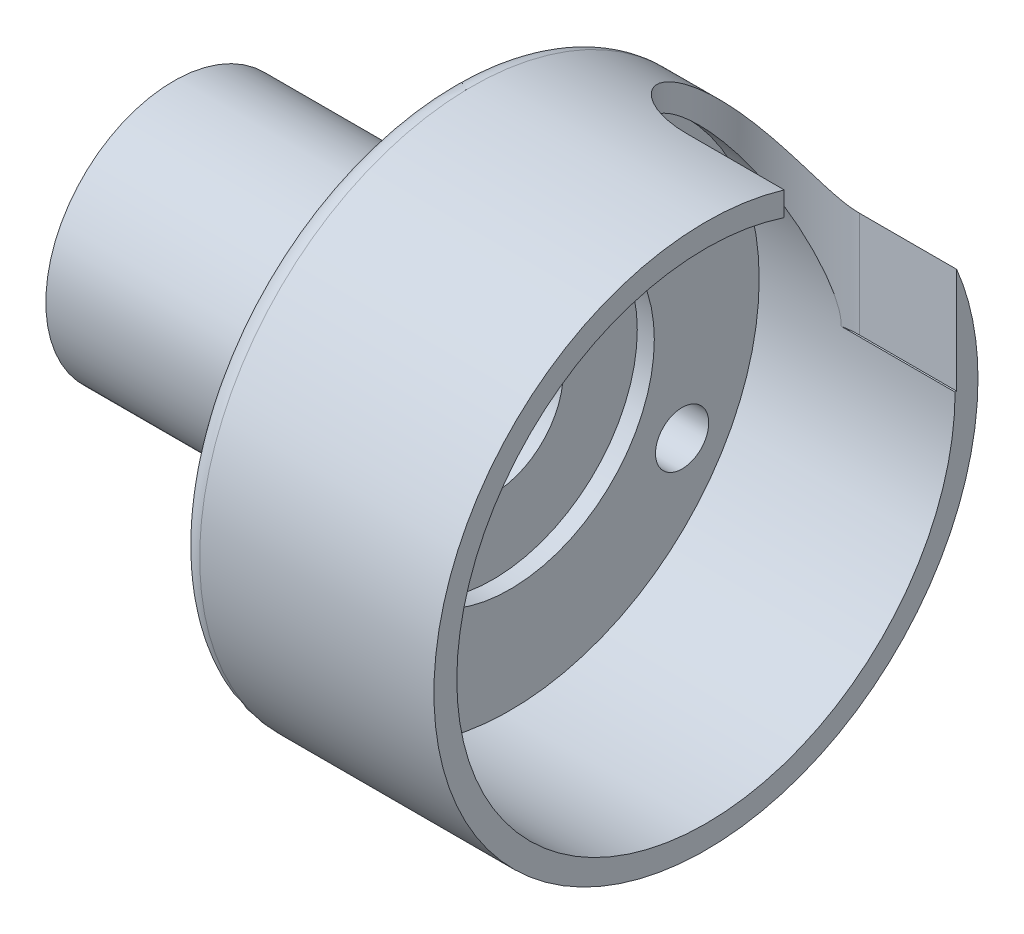
SolidWorks part; units mm, degrees
ref_plane "Front Plane" through (0, 0, 0) normal (0, 0, 1) x (1, 0, 0)
ref_plane "Top Plane" through (0, 0, 0) normal (0, 1, 0) x (1, 0, 0)
ref_plane "Right Plane" through (0, 0, 0) normal (1, 0, 0) x (0, 0, -1)
sketch "Sketch3" plane through (0, 0, 0) normal (1, 0, 0) x (0, 0, -1)
  circle A0 centre (0, 0) radius 6
  circle A1 centre (0, 0) radius 3.3
  dimension "D1" = 12
  dimension "D2" = 6.6
extrude "Boss-Extrude3" add sketch "Sketch3" along normal blind 10 and the other way blind 5 contours A1 | A0
sketch "Sketch10" plane through (10, 0, 0) normal (1, 0, 0) x (0, 0, -1)
  circle A0 centre (0, 0) radius 12.775
  circle A1 centre (0, 0) radius 2.1
  circle A2 centre (0, 0) radius 3.65
  dimension "D1" = 1.55
  dimension "D2" = 4.2
  dimension "D3" = 25.55
extrude "Boss-Extrude5" add sketch "Sketch10" against normal blind 2 contours A0
sketch "Sketch11" plane through (10, 0, 0) normal (1, 0, 0) x (0, 0, -1)
  circle A0 centre (0, 0) radius 6.775
  circle A1 centre (0, 0) radius 11.275
  circle M2 centre (0, 0) radius 3.3
  dimension "D1" = 13.55
  dimension "D2" = 22.55
extrude "Boss-Extrude6" add sketch "Sketch11" along normal blind 0.8 contours M2 | A0 M2 | A1
sketch "Sketch12" plane through (10.8, 0, 0) normal (1, 0, 0) x (0, 0, -1)
  line L1 (0, 9.33) -> (-8.08, -4.665)
  line L2 (-8.08, -4.665) -> (8.08, -4.665)
  line L3 (8.08, -4.665) -> (0, 9.33)
  circle A0 centre (0, 0) radius 4.665 construction
  circle A1 centre (0, 0) radius 11.275 construction
  circle A2 centre (-8.08, -4.665) radius 1.25
  circle A3 centre (8.08, -4.665) radius 1.25
  circle A4 centre (0, 9.33) radius 1.25
  dimension "D2" = 2.5
  dimension "D3" = 2.5
  dimension "D4" = 2.5
  dimension "D1" = 9.33
extrude "Cut-Extrude2" cut sketch "Sketch12" against normal blind 2.75 contours L2 A3 L3 | L3 A4 L1 | L1 A4 L3 | L3 A3 L2 | A2
fillet "Fillet3" radius 1 1 edges at (8, 0, -12.775)
sketch "Sketch13" plane through (10, 0, 0) normal (1, 0, 0) x (0, 0, -1)
  circle A0 centre (0, 0) radius 11.275 construction
  circle A1 centre (0, 0) radius 11.275
  circle A2 centre (0, 0) radius 12.775 construction
  circle A3 centre (0, 0) radius 12.775
extrude "Boss-Extrude7" add sketch "Sketch13" along normal blind 10
sketch "Sketch14" plane through (20, 0, 0) normal (1, 0, 0) x (0, 0, -1)
  circle A0 centre (0, 0) radius 11.7
  dimension "D1" = 23.4
extrude "Cut-Extrude3" cut sketch "Sketch14" against normal up to surface (9.2 mm away) up to face at (10.8, 9.33, -1.25)
sketch "Sketch15" plane through (0, 0, 0) normal (0, 1, 0) x (1, 0, 0)
  line L0 (15.4301, 3.675) -> (20, 3.675)
  line L1 (20, -12.775) -> (20, 12.775) construction
  line L2 (15.4301, 11.775) -> (20, 11.775)
  line L3 (20, 11.775) -> (20, 3.675)
  line L4 (20, 12.775) -> (9, 12.775) construction
  line L5 (20, 12.775) -> (9, 12.775)
  arc A0 (15.4301, 11.775) -> (15.4301, 3.675) centre (15.4301, 7.725) ccw
  dimension "D1" = 8.1
  dimension "D2" = 1
extrude "Cut-Extrude5" cut sketch "Sketch15" along normal blind 16 contours L3 L0 A0 L2
sketch "Sketch16" plane through (-5, 0, 0) normal (-1, 0, 0) x (0, 0, 1)
  circle A0 centre (0, 0) radius 4.5
  dimension "D1" = 9
extrude "Cut-Extrude6" cut sketch "Sketch16" against normal blind 14
